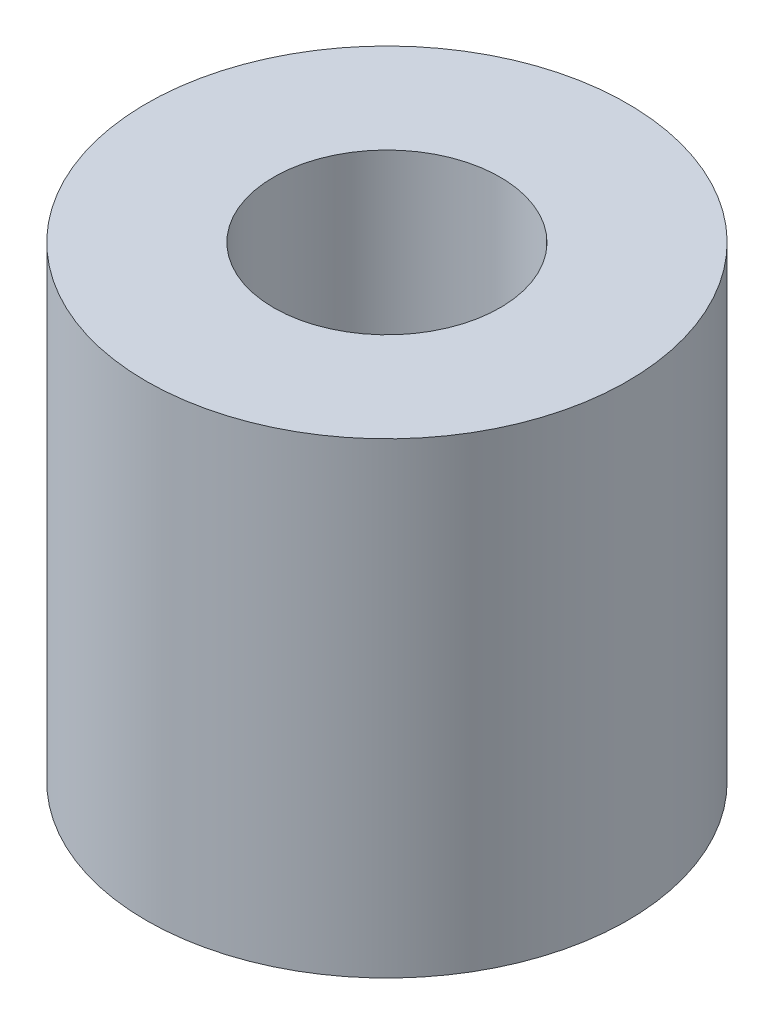
SolidWorks part; units mm, degrees
ref_plane "前视基准面" through (0, 0, 0) normal (0, 0, 1) x (1, 0, 0)
ref_plane "上视基准面" through (0, 0, 0) normal (0, 1, 0) x (1, 0, 0)
ref_plane "右视基准面" through (0, 0, 0) normal (1, 0, 0) x (0, 0, -1)
sketch "草图1" plane through (0, 0, 0) normal (0, 1, 0) x (1, 0, 0)
  circle A0 centre (0, 0) radius 8
  circle A1 centre (0, 0) radius 17
extrude "凸台-拉伸1" add sketch "草图1" along normal blind 33
